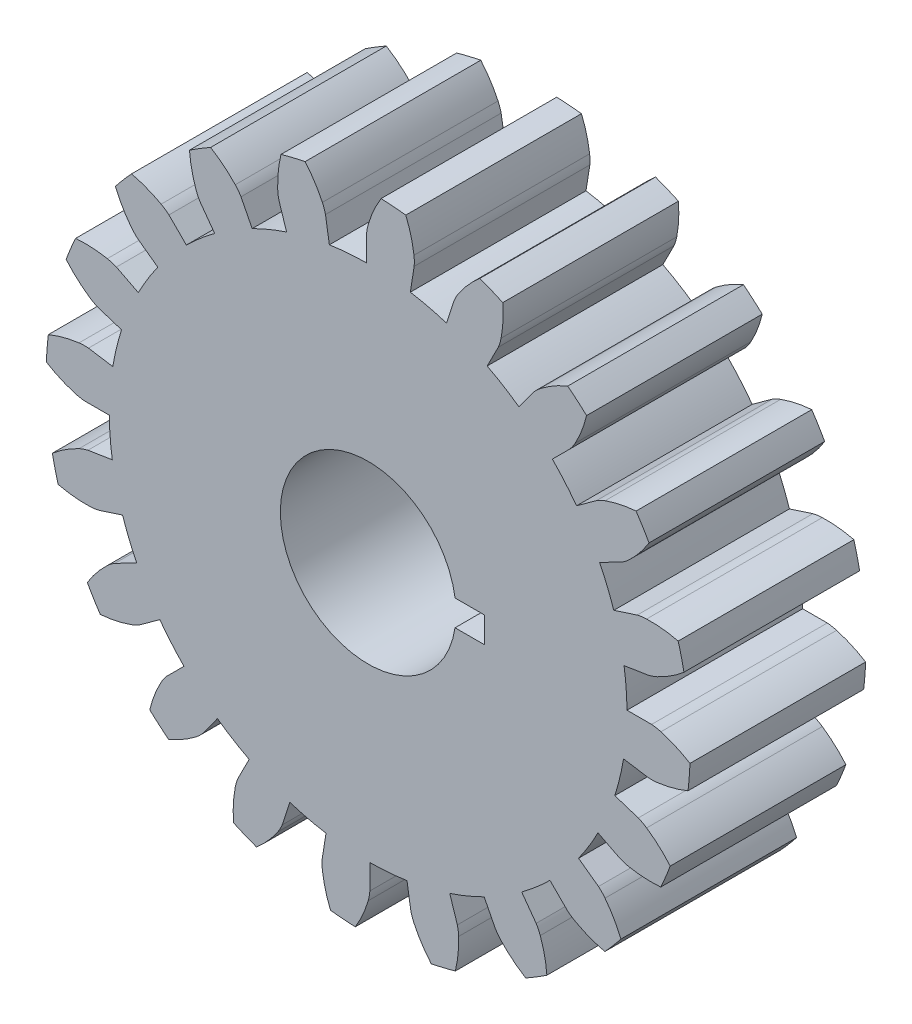
SolidWorks part; units mm, degrees
ref_plane "Front Plane" through (0, 0, 0) normal (0, 0, 1) x (1, 0, 0)
ref_plane "Top Plane" through (0, 0, 0) normal (0, 1, 0) x (1, 0, 0)
ref_plane "Right Plane" through (0, 0, 0) normal (1, 0, 0) x (0, 0, -1)
sketch "Sketch1" plane through (0, 0, 0) normal (0, 0, 1) x (1, 0, 0)
  line L0 (0, 3.8392) -> (0, -4.2373) construction
  line L1 (-5.1075, 0) -> (5.2668, 0) construction
  line L2 (-1.1302, 4.37) -> (1.0401, -4.022) construction
  line L3 (-0.606, 2.3433) -> (0, 2.5) construction
  line L4 (0, 2.5) -> (0.3911, 2.4692) construction
  line L5 (0, 0) -> (0.1955, 2.4846) construction
  line L6 (-0.0144, 2.4203) -> (-0.0144, 2.21)
  line L7 (0.3928, 2.3883) -> (0.3599, 2.1805)
  line L8 (0.7342, 2.3063) -> (0.6692, 2.1062)
  line L9 (1.1116, 2.15) -> (1.0161, 1.9625)
  line L10 (1.411, 1.9665) -> (1.2873, 1.7963)
  line L11 (1.7216, 1.7013) -> (1.5728, 1.5525)
  line L12 (1.9496, 1.4343) -> (1.7794, 1.3106)
  line L13 (2.1631, 1.086) -> (1.9756, 0.9905)
  line L14 (2.2974, 0.7616) -> (2.0973, 0.6966)
  line L15 (2.3928, 0.3644) -> (2.185, 0.3315)
  line L16 (2.4203, 0.0144) -> (2.21, 0.0144)
  line L17 (2.3883, -0.3928) -> (2.1805, -0.3599)
  line L18 (2.3063, -0.7342) -> (2.1062, -0.6692)
  line L19 (2.15, -1.1116) -> (1.9625, -1.0161)
  line L20 (1.9665, -1.411) -> (1.7963, -1.2873)
  line L21 (1.7013, -1.7216) -> (1.5525, -1.5728)
  line L22 (1.4343, -1.9496) -> (1.3106, -1.7794)
  line L23 (1.086, -2.1631) -> (0.9905, -1.9756)
  line L24 (0.7616, -2.2974) -> (0.6966, -2.0973)
  line L25 (0.3644, -2.3928) -> (0.3315, -2.185)
  line L26 (0.0144, -2.4203) -> (0.0144, -2.21)
  line L27 (-0.3928, -2.3883) -> (-0.3599, -2.1805)
  line L28 (-0.7342, -2.3063) -> (-0.6692, -2.1062)
  line L29 (-1.1116, -2.15) -> (-1.0161, -1.9625)
  line L30 (-1.411, -1.9665) -> (-1.2873, -1.7963)
  line L31 (-1.7216, -1.7013) -> (-1.5728, -1.5525)
  line L32 (-1.9496, -1.4343) -> (-1.7794, -1.3106)
  line L33 (-2.1631, -1.086) -> (-1.9756, -0.9905)
  line L34 (-2.2974, -0.7616) -> (-2.0973, -0.6966)
  line L35 (-2.3928, -0.3644) -> (-2.185, -0.3315)
  line L36 (-2.4203, -0.0144) -> (-2.21, -0.0144)
  line L37 (-2.3883, 0.3928) -> (-2.1805, 0.3599)
  line L38 (-2.3063, 0.7342) -> (-2.1062, 0.6692)
  line L39 (-2.15, 1.1116) -> (-1.9625, 1.0161)
  line L40 (-1.9665, 1.411) -> (-1.7963, 1.2873)
  line L41 (-1.7013, 1.7216) -> (-1.5525, 1.5728)
  line L42 (-1.4343, 1.9496) -> (-1.3106, 1.7794)
  line L43 (-1.086, 2.1631) -> (-0.9905, 1.9756)
  line L44 (-0.7616, 2.2974) -> (-0.6966, 2.0973)
  line L45 (-0.3644, 2.3928) -> (-0.3315, 2.185)
  line L46 (0.7419, 0.1101) -> (0.9919, 0.1101)
  line L47 (0.9919, 0.1101) -> (0.9919, -0.1101)
  line L48 (0.9919, -0.1101) -> (0.7419, -0.1101)
  arc A0 (0.3211, 2.7312) -> (0.1101, 2.7478) centre (0, 0) ccw
  circle A1 centre (0, 0) radius 2.5 construction
  arc A2 (-0.0144, 2.21) -> (-0.3315, 2.185) centre (0, 0) ccw
  arc A3 (1.9665, -1.411) -> (1.7013, -1.7216) centre (0, 0) ccw construction
  arc A4 (0, 2.5) -> (0.1101, 2.7478) centre (0.9651, 2.2196) cw
  arc A5 (0, 2.5) -> (-0.0144, 2.4203) centre (0.3745, 2.3912) ccw
  arc A6 (0.3911, 2.4692) -> (0.3928, 2.3883) centre (0.0042, 2.4204) cw
  arc A7 (0.3911, 2.4692) -> (0.3211, 2.7312) centre (-0.606, 2.3433) ccw
  arc A8 (0, 2.75) -> (2.75, 0) centre (0, 0) ccw construction
  arc A9 (0.7725, 2.3776) -> (0.9538, 2.5793) centre (1.6038, 1.8128) cw
  arc A10 (0.7725, 2.3776) -> (0.7342, 2.3063) centre (1.0951, 2.1584) ccw
  arc A11 (1.1494, 2.4983) -> (0.9538, 2.5793) centre (0, 0) ccw
  arc A12 (1.135, 2.2275) -> (1.1494, 2.4983) centre (0.1478, 2.4159) ccw
  arc A13 (1.135, 2.2275) -> (1.1116, 2.15) centre (0.7519, 2.3006) cw
  arc A14 (1.4695, 2.0225) -> (1.7042, 2.1583) centre (2.0854, 1.2284) cw
  arc A15 (1.4695, 2.0225) -> (1.411, 1.9665) centre (1.7085, 1.7144) ccw
  arc A16 (1.8652, 2.0208) -> (1.7042, 2.1583) centre (0, 0) ccw
  arc A17 (1.7678, 1.7678) -> (1.8652, 2.0208) centre (0.8871, 2.2519) ccw
  arc A18 (1.7678, 1.7678) -> (1.7216, 1.7013) centre (1.426, 1.9557) cw
  arc A19 (2.0225, 1.4695) -> (2.2877, 1.5261) centre (2.363, 0.5239) cw
  arc A20 (2.0225, 1.4695) -> (1.9496, 1.4343) centre (2.1547, 1.1025) ccw
  arc A21 (2.3983, 1.3456) -> (2.2877, 1.5261) centre (0, 0) ccw
  arc A22 (2.2275, 1.135) -> (2.3983, 1.3456) centre (1.5396, 1.8676) ccw
  arc A23 (2.2275, 1.135) -> (2.1631, 1.086) centre (1.9606, 1.4193) cw
  arc A24 (2.3776, 0.7725) -> (2.6473, 0.7444) centre (2.4092, -0.232) cw
  arc A25 (2.3776, 0.7725) -> (2.2974, 0.7616) centre (2.3899, 0.3827) ccw
  arc A26 (2.6967, 0.5386) -> (2.6473, 0.7444) centre (0, 0) ccw
  arc A27 (2.4692, 0.3911) -> (2.6967, 0.5386) centre (2.0413, 1.3004) ccw
  arc A28 (2.4692, 0.3911) -> (2.3928, 0.3644) centre (2.3032, 0.744) cw
  arc A29 (2.5, 0) -> (2.7478, -0.1101) centre (2.2196, -0.9651) cw
  arc A30 (2.5, 0) -> (2.4203, 0.0144) centre (2.3912, -0.3745) ccw
  arc A31 (2.7312, -0.3211) -> (2.7478, -0.1101) centre (0, 0) ccw
  arc A32 (2.4692, -0.3911) -> (2.7312, -0.3211) centre (2.3433, 0.606) ccw
  arc A33 (2.4692, -0.3911) -> (2.3883, -0.3928) centre (2.4204, -0.0042) cw
  arc A34 (2.3776, -0.7725) -> (2.5793, -0.9538) centre (1.8128, -1.6038) cw
  arc A35 (2.3776, -0.7725) -> (2.3063, -0.7342) centre (2.1584, -1.0951) ccw
  arc A36 (2.4983, -1.1494) -> (2.5793, -0.9538) centre (0, 0) ccw
  arc A37 (2.2275, -1.135) -> (2.4983, -1.1494) centre (2.4159, -0.1478) ccw
  arc A38 (2.2275, -1.135) -> (2.15, -1.1116) centre (2.3006, -0.7519) cw
  arc A39 (2.0225, -1.4695) -> (2.1583, -1.7042) centre (1.2284, -2.0854) cw
  arc A40 (2.0225, -1.4695) -> (1.9665, -1.411) centre (1.7144, -1.7085) ccw
  arc A41 (2.0208, -1.8652) -> (2.1583, -1.7042) centre (0, 0) ccw
  arc A42 (1.7678, -1.7678) -> (2.0208, -1.8652) centre (2.2519, -0.8871) ccw
  arc A43 (1.7678, -1.7678) -> (1.7013, -1.7216) centre (1.9557, -1.426) cw
  arc A44 (1.4695, -2.0225) -> (1.5261, -2.2877) centre (0.5239, -2.363) cw
  arc A45 (1.4695, -2.0225) -> (1.4343, -1.9496) centre (1.1025, -2.1547) ccw
  arc A46 (1.3456, -2.3983) -> (1.5261, -2.2877) centre (0, 0) ccw
  arc A47 (1.135, -2.2275) -> (1.3456, -2.3983) centre (1.8676, -1.5396) ccw
  arc A48 (1.135, -2.2275) -> (1.086, -2.1631) centre (1.4193, -1.9606) cw
  arc A49 (0.7725, -2.3776) -> (0.7444, -2.6473) centre (-0.232, -2.4092) cw
  arc A50 (0.7725, -2.3776) -> (0.7616, -2.2974) centre (0.3827, -2.3899) ccw
  arc A51 (0.5386, -2.6967) -> (0.7444, -2.6473) centre (0, 0) ccw
  arc A52 (0.3911, -2.4692) -> (0.5386, -2.6967) centre (1.3004, -2.0413) ccw
  arc A53 (0.3911, -2.4692) -> (0.3644, -2.3928) centre (0.744, -2.3032) cw
  arc A54 (0, -2.5) -> (-0.1101, -2.7478) centre (-0.9651, -2.2196) cw
  arc A55 (0, -2.5) -> (0.0144, -2.4203) centre (-0.3745, -2.3912) ccw
  arc A56 (-0.3211, -2.7312) -> (-0.1101, -2.7478) centre (0, 0) ccw
  arc A57 (-0.3911, -2.4692) -> (-0.3211, -2.7312) centre (0.606, -2.3433) ccw
  arc A58 (-0.3911, -2.4692) -> (-0.3928, -2.3883) centre (-0.0042, -2.4204) cw
  arc A59 (-0.7725, -2.3776) -> (-0.9538, -2.5793) centre (-1.6038, -1.8128) cw
  arc A60 (-0.7725, -2.3776) -> (-0.7342, -2.3063) centre (-1.0951, -2.1584) ccw
  arc A61 (-1.1494, -2.4983) -> (-0.9538, -2.5793) centre (0, 0) ccw
  arc A62 (-1.135, -2.2275) -> (-1.1494, -2.4983) centre (-0.1478, -2.4159) ccw
  arc A63 (-1.135, -2.2275) -> (-1.1116, -2.15) centre (-0.7519, -2.3006) cw
  arc A64 (-1.4695, -2.0225) -> (-1.7042, -2.1583) centre (-2.0854, -1.2284) cw
  arc A65 (-1.4695, -2.0225) -> (-1.411, -1.9665) centre (-1.7085, -1.7144) ccw
  arc A66 (-1.8652, -2.0208) -> (-1.7042, -2.1583) centre (0, 0) ccw
  arc A67 (-1.7678, -1.7678) -> (-1.8652, -2.0208) centre (-0.8871, -2.2519) ccw
  arc A68 (-1.7678, -1.7678) -> (-1.7216, -1.7013) centre (-1.426, -1.9557) cw
  arc A69 (-2.0225, -1.4695) -> (-2.2877, -1.5261) centre (-2.363, -0.5239) cw
  arc A70 (-2.0225, -1.4695) -> (-1.9496, -1.4343) centre (-2.1547, -1.1025) ccw
  arc A71 (-2.3983, -1.3456) -> (-2.2877, -1.5261) centre (0, 0) ccw
  arc A72 (-2.2275, -1.135) -> (-2.3983, -1.3456) centre (-1.5396, -1.8676) ccw
  arc A73 (-2.2275, -1.135) -> (-2.1631, -1.086) centre (-1.9606, -1.4193) cw
  arc A74 (-2.3776, -0.7725) -> (-2.6473, -0.7444) centre (-2.4092, 0.232) cw
  arc A75 (-2.3776, -0.7725) -> (-2.2974, -0.7616) centre (-2.3899, -0.3827) ccw
  arc A76 (-2.6967, -0.5386) -> (-2.6473, -0.7444) centre (0, 0) ccw
  arc A77 (-2.4692, -0.3911) -> (-2.6967, -0.5386) centre (-2.0413, -1.3004) ccw
  arc A78 (-2.4692, -0.3911) -> (-2.3928, -0.3644) centre (-2.3032, -0.744) cw
  arc A79 (-2.5, 0) -> (-2.7478, 0.1101) centre (-2.2196, 0.9651) cw
  arc A80 (-2.5, 0) -> (-2.4203, -0.0144) centre (-2.3912, 0.3745) ccw
  arc A81 (-2.7312, 0.3211) -> (-2.7478, 0.1101) centre (0, 0) ccw
  arc A82 (-2.4692, 0.3911) -> (-2.7312, 0.3211) centre (-2.3433, -0.606) ccw
  arc A83 (-2.4692, 0.3911) -> (-2.3883, 0.3928) centre (-2.4204, 0.0042) cw
  arc A84 (-2.3776, 0.7725) -> (-2.5793, 0.9538) centre (-1.8128, 1.6038) cw
  arc A85 (-2.3776, 0.7725) -> (-2.3063, 0.7342) centre (-2.1584, 1.0951) ccw
  arc A86 (-2.4983, 1.1494) -> (-2.5793, 0.9538) centre (0, 0) ccw
  arc A87 (-2.2275, 1.135) -> (-2.4983, 1.1494) centre (-2.4159, 0.1478) ccw
  arc A88 (-2.2275, 1.135) -> (-2.15, 1.1116) centre (-2.3006, 0.7519) cw
  arc A89 (-2.0225, 1.4695) -> (-2.1583, 1.7042) centre (-1.2284, 2.0854) cw
  arc A90 (-2.0225, 1.4695) -> (-1.9665, 1.411) centre (-1.7144, 1.7085) ccw
  arc A91 (-2.0208, 1.8652) -> (-2.1583, 1.7042) centre (0, 0) ccw
  arc A92 (-1.7678, 1.7678) -> (-2.0208, 1.8652) centre (-2.2519, 0.8871) ccw
  arc A93 (-1.7678, 1.7678) -> (-1.7013, 1.7216) centre (-1.9557, 1.426) cw
  arc A94 (-1.4695, 2.0225) -> (-1.5261, 2.2877) centre (-0.5239, 2.363) cw
  arc A95 (-1.4695, 2.0225) -> (-1.4343, 1.9496) centre (-1.1025, 2.1547) ccw
  arc A96 (-1.3456, 2.3983) -> (-1.5261, 2.2877) centre (0, 0) ccw
  arc A97 (-1.135, 2.2275) -> (-1.3456, 2.3983) centre (-1.8676, 1.5396) ccw
  arc A98 (-1.135, 2.2275) -> (-1.086, 2.1631) centre (-1.4193, 1.9606) cw
  arc A99 (-0.7725, 2.3776) -> (-0.7444, 2.6473) centre (0.232, 2.4092) cw
  arc A100 (-0.7725, 2.3776) -> (-0.7616, 2.2974) centre (-0.3827, 2.3899) ccw
  arc A101 (-0.5386, 2.6967) -> (-0.7444, 2.6473) centre (0, 0) ccw
  arc A102 (-0.3911, 2.4692) -> (-0.5386, 2.6967) centre (-1.3004, 2.0413) ccw
  arc A103 (-0.3911, 2.4692) -> (-0.3644, 2.3928) centre (-0.744, 2.3032) cw
  arc A104 (-0.6966, 2.0973) -> (-0.9905, 1.9756) centre (0, 0) ccw
  arc A105 (-1.3106, 1.7794) -> (-1.5525, 1.5728) centre (0, 0) ccw
  arc A106 (-1.7963, 1.2873) -> (-1.9625, 1.0161) centre (0, 0) ccw
  arc A107 (-2.1062, 0.6692) -> (-2.1805, 0.3599) centre (0, 0) ccw
  arc A108 (-2.21, -0.0144) -> (-2.185, -0.3315) centre (0, 0) ccw
  arc A109 (-2.0973, -0.6966) -> (-1.9756, -0.9905) centre (0, 0) ccw
  arc A110 (-1.7794, -1.3106) -> (-1.5728, -1.5525) centre (0, 0) ccw
  arc A111 (-1.2873, -1.7963) -> (-1.0161, -1.9625) centre (0, 0) ccw
  arc A112 (-0.6692, -2.1062) -> (-0.3599, -2.1805) centre (0, 0) ccw
  arc A113 (0.0144, -2.21) -> (0.3315, -2.185) centre (0, 0) ccw
  arc A114 (0.6966, -2.0973) -> (0.9905, -1.9756) centre (0, 0) ccw
  arc A115 (1.3106, -1.7794) -> (1.5525, -1.5728) centre (0, 0) ccw
  arc A116 (1.7963, -1.2873) -> (1.9625, -1.0161) centre (0, 0) ccw
  arc A117 (2.1062, -0.6692) -> (2.1805, -0.3599) centre (0, 0) ccw
  arc A118 (2.21, 0.0144) -> (2.185, 0.3315) centre (0, 0) ccw
  arc A119 (2.0973, 0.6966) -> (1.9756, 0.9905) centre (0, 0) ccw
  arc A120 (1.7794, 1.3106) -> (1.5728, 1.5525) centre (0, 0) ccw
  arc A121 (1.2873, 1.7963) -> (1.0161, 1.9625) centre (0, 0) ccw
  arc A122 (0.6692, 2.1062) -> (0.3599, 2.1805) centre (0, 0) ccw
  arc A123 (0.7419, 0.1101) -> (0.7419, -0.1101) centre (0, 0) ccw
  point P11 (0, 2.5)
  point P14 (0.3911, 2.4692)
  point P15 (0.7725, 2.3776)
  point P16 (1.135, 2.2275)
  point P17 (1.4695, 2.0225)
  point P18 (1.7678, 1.7678)
  point P19 (2.0225, 1.4695)
  point P20 (2.2275, 1.135)
  point P21 (2.3776, 0.7725)
  point P22 (2.4692, 0.3911)
  point P23 (2.5, 0)
  point P24 (2.4692, -0.3911)
  point P25 (2.3776, -0.7725)
  point P26 (2.2275, -1.135)
  point P27 (2.0225, -1.4695)
  point P28 (1.7678, -1.7678)
  point P29 (1.4695, -2.0225)
  point P30 (1.135, -2.2275)
  point P31 (0.7725, -2.3776)
  point P32 (0.3911, -2.4692)
  point P33 (0, -2.5)
  point P34 (-0.3911, -2.4692)
  point P35 (-0.7725, -2.3776)
  point P36 (-1.135, -2.2275)
  point P37 (-1.4695, -2.0225)
  point P38 (-1.7678, -1.7678)
  point P39 (-2.0225, -1.4695)
  point P40 (-2.2275, -1.135)
  point P41 (-2.3776, -0.7725)
  point P42 (-2.4692, -0.3911)
  point P43 (-2.5, 0)
  point P44 (-2.4692, 0.3911)
  point P45 (-2.3776, 0.7725)
  point P46 (-2.2275, 1.135)
  point P47 (-2.0225, 1.4695)
  point P48 (-1.7678, 1.7678)
  point P49 (-1.4695, 2.0225)
  point P50 (-1.135, 2.2275)
  point P51 (-0.7725, 2.3776)
  point P52 (-0.3911, 2.4692)
  point P53 (0, 0)
  point P298 (0, 0)
  dimension "D1" = 5.5
  dimension "D2" = 5
  dimension "D3" = 4.42
  dimension "D6" = 1.005
  dimension "D7" = 0.39
  dimension "D9" = 1.5
  dimension "D4" = 14.5
  dimension "D10" = 0.25
  dimension "D5" = 40
  dimension "D8" = 20
extrude "Boss-Extrude1" add sketch "Sketch1" along normal blind 1.5
